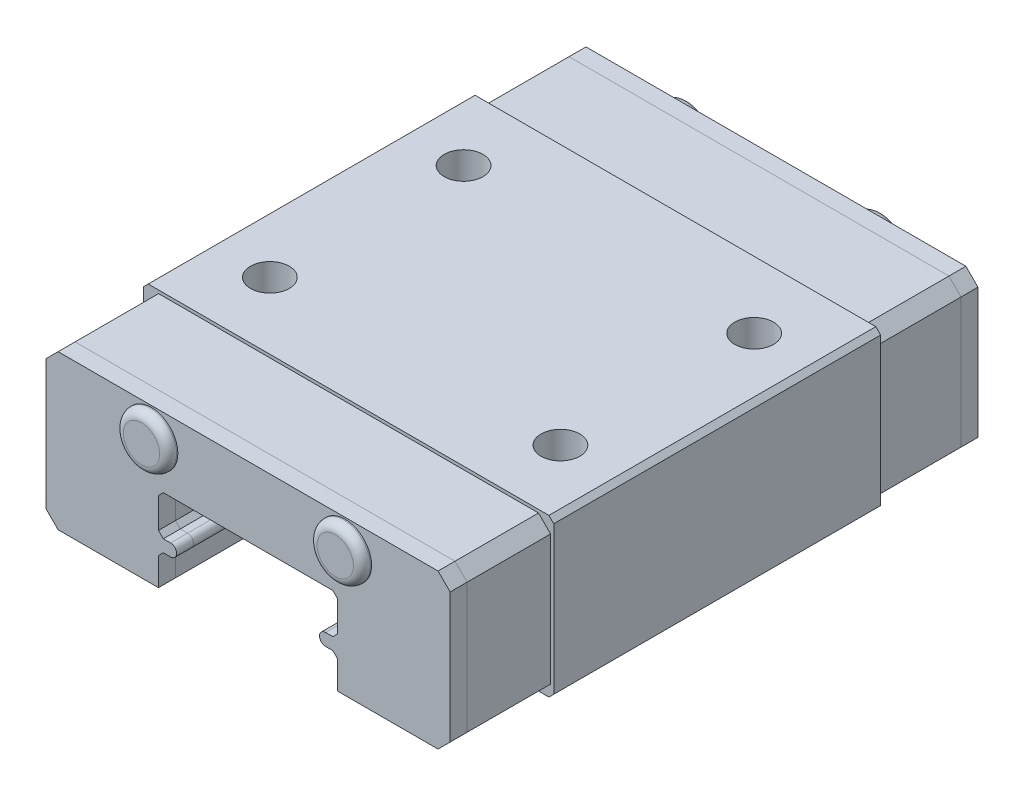
SolidWorks part; units mm, degrees
ref_plane "Front Plane" through (0, 0, 0) normal (0, 0, 1) x (1, 0, 0)
ref_plane "Top Plane" through (0, 0, 0) normal (0, 1, 0) x (1, 0, 0)
ref_plane "Right Plane" through (0, 0, 0) normal (1, 0, 0) x (0, 0, -1)
sketch "Sketch1" plane through (0, 0, 0) normal (0, 0, 1) x (1, 0, 0)
  line L0 (-8.475, 0) -> (8.475, 0)
  line L1 (8.475, 0) -> (8.475, 6.5)
  line L2 (8.475, 6.5) -> (-8.475, 6.5)
  line L3 (-8.475, 6.5) -> (-8.475, 0)
  point P4 (0, 0)
  dimension "D1" = 16.95
  dimension "D2" = 6.5
extrude "Boss-Extrude1" add sketch "Sketch1" along normal mid plane 13.5
sketch "Sketch2" plane through (0, 0, 6.75) normal (0, 0, 1) x (1, 0, 0)
  line L0 (-3.7, 0) -> (3.7, 0)
  line L1 (-8.475, 0) -> (8.475, 0) construction
  line L2 (-3.7, 0) -> (-3.7, 1.35)
  line L3 (-3.7, 3.5) -> (3.7, 3.5)
  line L4 (3.7, 3.5) -> (3.7, 1.85)
  line L5 (-3.7, 1.6) -> (-3.2, 1.6) construction
  line L6 (-3.7, 1.85) -> (-3.2, 1.85)
  line L7 (-3.7, 1.35) -> (-3.2, 1.35)
  line L8 (3.7, 1.6) -> (3.2, 1.6) construction
  line L9 (3.7, 1.35) -> (3.2, 1.35)
  line L10 (3.7, 1.85) -> (3.2, 1.85)
  line L11 (-3.7, 1.85) -> (-3.7, 3.5)
  line L12 (3.7, 1.35) -> (3.7, 0)
  arc A1 (-3.2, 1.35) -> (-3.2, 1.85) centre (-3.2, 1.6) ccw
  arc A3 (3.2, 1.85) -> (3.2, 1.35) centre (3.2, 1.6) ccw
  point P5 (0, 0)
  dimension "D1" = 3.5
  dimension "D2" = 7.4
  dimension "D3" = 0.5
  dimension "D4" = 1.9
  dimension "D5" = 0.5
extrude "Cut-Extrude1" cut sketch "Sketch2" against normal through all both and the other way through all
chamfer "Chamfer1" distance 0.2 angle 45 10 edges at (3.7, 1.35, 0) (3.7, 1.85, 0) (-3.7, 1.35, 0) (-3.7, 1.85, 0) (3.7, 3.5, 0) (-3.7, 3.5, 0) (-8.475, 0, 0) (8.475, 0, 0) (8.475, 6.5, 0) (-8.475, 6.5, 0)
hole_wizard "Tap Drill for M2x0.4 Tap1" positions "Sketch3" profile "Sketch4" hole size "M2x0.4" standard "ANSI Metric"
sketch "Sketch3" plane through (0, 6.5, 0) normal (0, 1, 0) x (1, 0, 0)
  line L1 (6, 4) -> (-6, 4) construction
  line L2 (6, 4) -> (6, -4) construction
  line L3 (6, -4) -> (-6, -4) construction
  line L4 (-6, 4) -> (-6, -4) construction
  line L5 (6, 4) -> (-6, -4) construction
  point P0 (-6, 4)
  point P3 (6, 4)
  point P4 (-6, -4)
  point P101 (6, -4)
  point P108 (0, 0)
  dimension "D1" = 8
  dimension "D2" = 12
sketch "Sketch4" plane through (-6, 6.5, -4) normal (1, 0, 0) x (0, 0, 1)
  line L0 (0, 0) -> (0, 4.9807)
  line L1 (0, 4.9807) -> (0.8, 4.5)
  line L2 (0.8, 4.5) -> (0.8, 0)
  line L5 (0.8, 0) -> (0, 0)
  line L10 (0, 4.9807) -> (-0.8, 4.5) construction
  line L11 (0, -6.35) -> (0, 107.95) construction
  dimension "Hole Dia." = 1.6
  dimension "Hole Depth" = 4.5
  dimension "Drill Angle" = 118
sketch "Sketch5" plane through (0, 0, 6.75) normal (0, 0, 1) x (1, 0, 0)
  line L0 (-8.275, 0) -> (-3.7, 0) construction
  line L1 (-8.345, 0) -> (-3.7, 0)
  line L2 (-8.345, 0) -> (-8.345, 6.37)
  line L3 (-8.345, 6.37) -> (8.345, 6.37)
  line L4 (8.345, 0) -> (8.345, 6.37)
  line L5 (8.275, 6.5) -> (-8.275, 6.5) construction
  line L6 (-8.475, 6.3) -> (-8.475, 0.2) construction
  line L7 (8.475, 0.2) -> (8.475, 6.3) construction
  line L8 (3.7, 0) -> (3.7, 1.15) construction
  line L9 (3.5, 1.35) -> (3.2, 1.35) construction
  line L10 (3.5, 1.35) -> (3.7, 1.15) construction
  line L11 (3.2, 1.85) -> (3.5, 1.85) construction
  line L12 (3.7, 2.05) -> (3.5, 1.85) construction
  line L13 (3.7, 2.05) -> (3.7, 3.3) construction
  line L14 (3.5, 3.5) -> (3.7, 3.3) construction
  line L15 (3.5, 3.5) -> (-3.5, 3.5) construction
  line L16 (-3.7, 3.3) -> (-3.5, 3.5) construction
  line L17 (-3.7, 3.3) -> (-3.7, 2.05) construction
  line L18 (-3.5, 1.85) -> (-3.7, 2.05) construction
  line L19 (-3.5, 1.85) -> (-3.2, 1.85) construction
  line L20 (-3.2, 1.35) -> (-3.5, 1.35) construction
  line L21 (-3.7, 1.15) -> (-3.5, 1.35) construction
  line L22 (-3.7, 1.15) -> (-3.7, 0) construction
  line L23 (3.7, 0) -> (3.7, 1.15)
  line L24 (3.5, 1.35) -> (3.2, 1.35)
  line L25 (3.5, 1.35) -> (3.7, 1.15)
  line L26 (3.2, 1.85) -> (3.5, 1.85)
  line L27 (3.7, 2.05) -> (3.5, 1.85)
  line L28 (3.7, 2.05) -> (3.7, 3.3)
  line L29 (3.5, 3.5) -> (3.7, 3.3)
  line L30 (3.5, 3.5) -> (-3.5, 3.5)
  line L31 (-3.7, 3.3) -> (-3.5, 3.5)
  line L32 (-3.7, 3.3) -> (-3.7, 2.05)
  line L33 (-3.5, 1.85) -> (-3.7, 2.05)
  line L34 (-3.5, 1.85) -> (-3.2, 1.85)
  line L35 (-3.2, 1.35) -> (-3.5, 1.35)
  line L36 (-3.7, 1.15) -> (-3.5, 1.35)
  line L37 (-3.7, 1.15) -> (-3.7, 0)
  line L38 (3.7, 0) -> (8.345, 0)
  arc A0 (3.2, 1.85) -> (3.2, 1.35) centre (3.2, 1.6) ccw construction
  arc A1 (-3.2, 1.35) -> (-3.2, 1.85) centre (-3.2, 1.6) ccw construction
  arc A2 (3.2, 1.85) -> (3.2, 1.35) centre (3.2, 1.6) ccw
  arc A3 (-3.2, 1.35) -> (-3.2, 1.85) centre (-3.2, 1.6) ccw
  dimension "D1" = 0.13
  dimension "D2" = 0.13
  dimension "D3" = 0.13
extrude "Boss-Extrude2" add sketch "Sketch5" along normal blind 3.45 separate body contours L3 L4 L38 L23 L25 L24 A2 L26 L27 L28 L29 L30 L31 L32 L33 L34 A3 L35 L36 L37 L1 L2
chamfer "Chamfer2" distance 0.5 angle 45 4 edges at (-8.345, 0, 8.475) (8.345, 0, 8.475) (8.345, 6.37, 8.475) (-8.345, 6.37, 8.475)
sketch "Sketch6" plane through (0, 0, 10.2) normal (0, 0, 1) x (1, 0, 0)
  line L24 (-8.345, 5.87) -> (-8.345, 0.5)
  line L25 (-8.345, 0.5) -> (-7.845, 0)
  line L26 (-7.845, 0) -> (-3.7, 0)
  line L27 (-3.7, 0) -> (-3.7, 1.15)
  line L28 (-3.7, 1.15) -> (-3.5, 1.35)
  line L29 (-3.5, 1.35) -> (-3.2, 1.35)
  line L30 (-3.2, 1.85) -> (-3.5, 1.85)
  line L31 (-3.5, 1.85) -> (-3.7, 2.05)
  line L32 (-3.7, 2.05) -> (-3.7, 3.3)
  line L33 (-3.7, 3.3) -> (-3.5, 3.5)
  line L34 (-3.5, 3.5) -> (3.5, 3.5)
  line L35 (3.5, 3.5) -> (3.7, 3.3)
  line L36 (3.7, 3.3) -> (3.7, 2.05)
  line L37 (3.7, 2.05) -> (3.5, 1.85)
  line L38 (3.5, 1.85) -> (3.2, 1.85)
  line L39 (3.2, 1.35) -> (3.5, 1.35)
  line L40 (3.5, 1.35) -> (3.7, 1.15)
  line L41 (3.7, 1.15) -> (3.7, 0)
  line L42 (3.7, 0) -> (7.845, 0)
  line L43 (7.845, 0) -> (8.345, 0.5)
  line L44 (8.345, 0.5) -> (8.345, 5.87)
  line L45 (8.345, 5.87) -> (7.845, 6.37)
  line L46 (7.845, 6.37) -> (-7.845, 6.37)
  line L47 (-7.845, 6.37) -> (-8.345, 5.87)
  line L48 (-8.345, 5.87) -> (-8.345, 0.5)
  line L49 (-8.345, 0.5) -> (-7.845, 0)
  line L50 (-7.845, 0) -> (-3.7, 0)
  line L51 (-3.7, 0) -> (-3.7, 1.15)
  line L52 (-3.7, 1.15) -> (-3.5, 1.35)
  line L53 (-3.5, 1.35) -> (-3.2, 1.35)
  line L54 (-3.2, 1.85) -> (-3.5, 1.85)
  line L55 (-3.5, 1.85) -> (-3.7, 2.05)
  line L56 (-3.7, 2.05) -> (-3.7, 3.3)
  line L57 (-3.7, 3.3) -> (-3.5, 3.5)
  line L58 (-3.5, 3.5) -> (3.5, 3.5)
  line L59 (3.5, 3.5) -> (3.7, 3.3)
  line L60 (3.7, 3.3) -> (3.7, 2.05)
  line L61 (3.7, 2.05) -> (3.5, 1.85)
  line L62 (3.5, 1.85) -> (3.2, 1.85)
  line L63 (3.2, 1.35) -> (3.5, 1.35)
  line L64 (3.5, 1.35) -> (3.7, 1.15)
  line L65 (3.7, 1.15) -> (3.7, 0)
  line L66 (3.7, 0) -> (7.845, 0)
  line L67 (7.845, 0) -> (8.345, 0.5)
  line L68 (8.345, 0.5) -> (8.345, 5.87)
  line L69 (8.345, 5.87) -> (7.845, 6.37)
  line L70 (7.845, 6.37) -> (-7.845, 6.37)
  line L71 (-7.845, 6.37) -> (-8.345, 5.87)
  arc A2 (-3.2, 1.35) -> (-3.2, 1.85) centre (-3.2, 1.6) ccw
  arc A3 (3.2, 1.85) -> (3.2, 1.35) centre (3.2, 1.6) ccw
  arc A4 (-3.2, 1.35) -> (-3.2, 1.85) centre (-3.2, 1.6) ccw
  arc A5 (3.2, 1.85) -> (3.2, 1.35) centre (3.2, 1.6) ccw
  dimension "D1" = 0
extrude "Boss-Extrude3" add sketch "Sketch6" along normal blind 0.7 separate body
sketch "Sketch7" plane through (0, 0, 10.9) normal (0, 0, 1) x (1, 0, 0)
  line L0 (-4, 5.2) -> (4, 5.2) construction
  line L1 (0, 5.2) -> (0, 0) construction
  line L2 (8.275, 6.5) -> (-8.275, 6.5) construction
  circle A0 centre (-4, 5.2) radius 1.1
  circle A1 centre (4, 5.2) radius 1.1
  dimension "D3" = 2.2
  dimension "D1" = 8
  dimension "D2" = 1.3
extrude "Boss-Extrude4" add sketch "Sketch7" along normal blind 0.4 separate body
fillet "Fillet1" radius 0.35 1 edges at (-2.9, 5.2, 11.3)
fillet "Fillet2" radius 0.35 1 edges at (5.1, 5.2, 11.3)
mirror "Mirror1" about plane through (0, 0, 0) normal (0, 0, 1) of bodies 113 114 116 115
